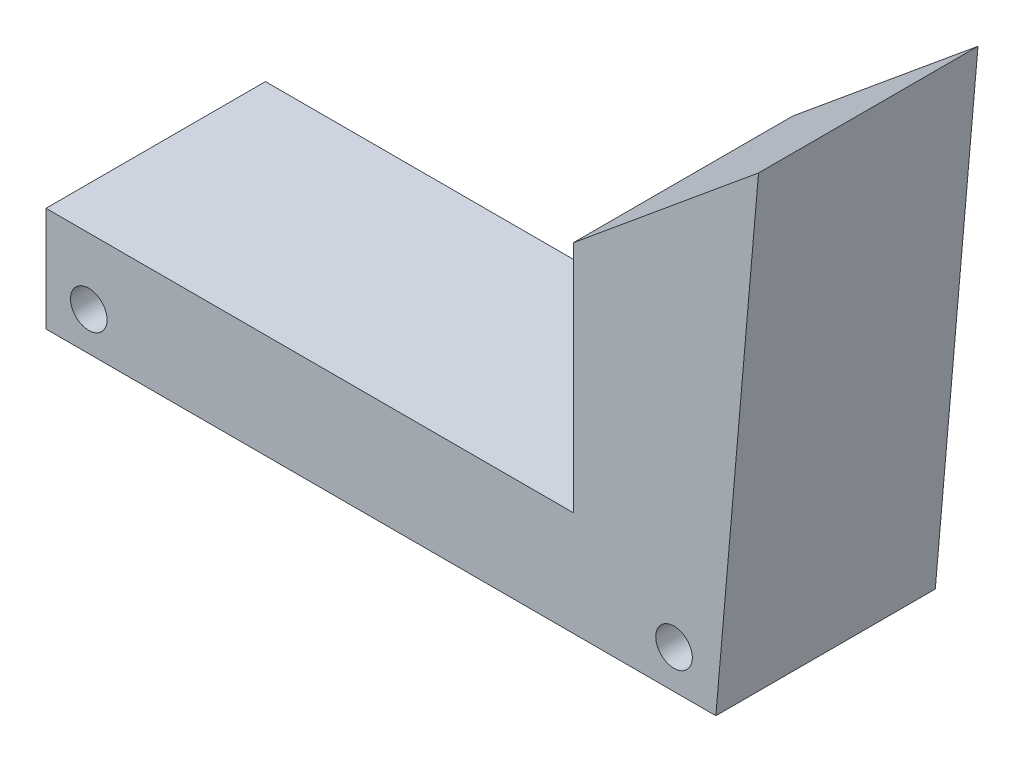
SolidWorks part; units mm, degrees
ref_plane "Front Plane" through (0, 0, 0) normal (0, 0, 1) x (1, 0, 0)
ref_plane "Top Plane" through (0, 0, 0) normal (0, 1, 0) x (1, 0, 0)
ref_plane "Right Plane" through (0, 0, 0) normal (1, 0, 0) x (0, 0, -1)
sketch "Sketch1" plane through (0, 0, 0) normal (0, 0, 1) x (1, 0, 0)
  line L0 (-16.0567, 2.7332) -> (100.2257, 2.7332)
  line L1 (100.2257, 2.7332) -> (107.6366, 88.047)
  line L2 (107.6366, 88.047) -> (75.4919, 61.4904)
  line L3 (75.4919, 61.4904) -> (75.4919, 20.887)
  line L4 (75.4919, 20.887) -> (-16.0567, 20.887)
  line L5 (-16.0567, 20.887) -> (-16.0567, 2.7332)
  circle A0 centre (-8.6342, 9.4124) radius 3.175
  circle A1 centre (92.9658, 9.4124) radius 3.175
  dimension "D1" = 101.6
  dimension "D2" = 6.35
  dimension "D3" = 6.35
extrude "Boss-Extrude1" add sketch "Sketch1" along normal blind 38.1
